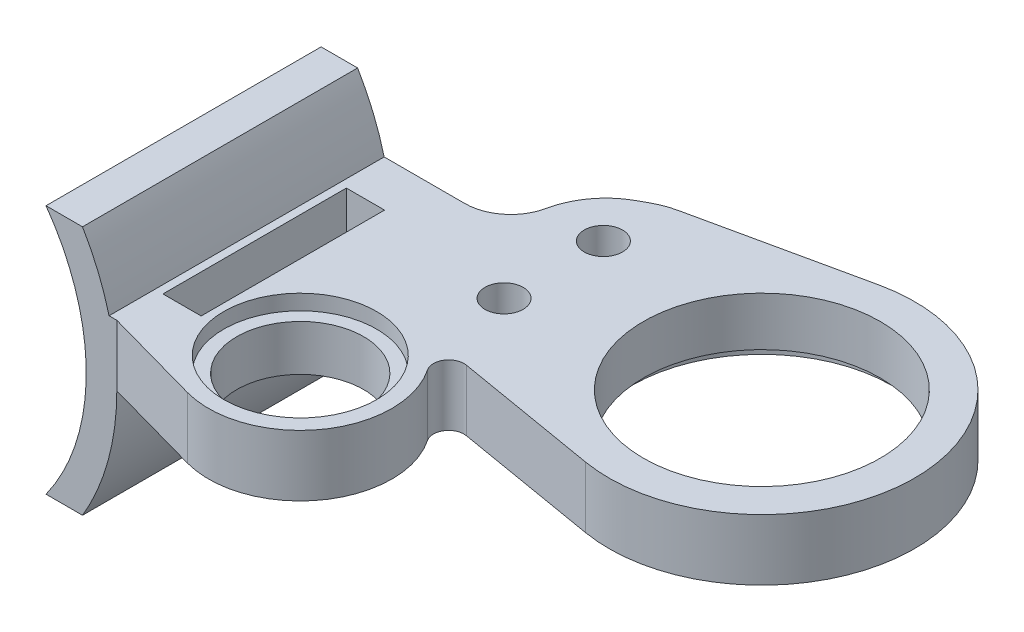
SolidWorks part; units mm, degrees
ref_plane "Front Plane" through (0, 0, 0) normal (0, 0, 1) x (1, 0, 0)
ref_plane "Top Plane" through (0, 0, 0) normal (0, 1, 0) x (1, 0, 0)
ref_plane "Right Plane" through (0, 0, 0) normal (1, 0, 0) x (0, 0, -1)
sketch "草图1" plane through (0, 0, 0) normal (0, 0, 1) x (1, 0, 0)
  line L6 (13.755, 8.1732) -> (11.3666, 8.1732)
  line L7 (11.3666, -8.1732) -> (13.755, -8.1732)
  arc A0 (11.3666, 8.1732) -> (11.3666, -8.1732) centre (0, 0) cw
  arc A1 (13.755, 8.1732) -> (13.755, -8.1732) centre (0, 0) cw
  dimension "D1" = 14
  dimension "D2" = 16
extrude "凸台-拉伸1" add sketch "草图1" along normal blind 18
sketch "草图3" plane through (0, 0, 0) normal (0, 1, 0) x (1, 0, 0)
  line L1 (16, -18) -> (14.8775, -18)
  line L4 (16, -18) -> (22.39, -19.7799)
  line L5 (13.755, -18) -> (16, -18) construction
  line L6 (16, -18) -> (16, 0) construction
  line L7 (14.8775, -18) -> (14.8775, 0)
  line L8 (16, 0) -> (13.755, 0) construction
  line L9 (14.8775, 0) -> (16, 0)
  line L12 (16.0173, -15) -> (18.5173, -15)
  line L13 (16.0173, -15) -> (16.0173, -3)
  line L14 (16.0173, -3) -> (18.5173, -3)
  line L15 (18.5173, -15) -> (18.5173, -3)
  line L16 (16.0173, -15) -> (18.5173, -3) construction
  line L17 (16.0173, -3) -> (18.5173, -15) construction
  line L18 (39.371, -10.7007) -> (26.3968, -8.4995)
  line L23 (27.4261, 6.433) -> (38.9205, 8.9304)
  line L24 (27.4261, 12.6834) -> (27.4261, -9.9467) construction
  line L25 (16, 0) -> (23.607, 0)
  line L29 (23.607, 0) -> (23.607, 4.3535)
  line L30 (23.607, 4.3535) -> (27.4261, 6.433)
  circle A1 centre (24, -14) radius 4.15
  arc A3 (39.371, -10.7007) -> (38.9205, 8.9304) centre (41.0437, -0.8416) ccw
  circle A4 centre (41.0437, -0.8416) radius 7.75
  circle A9 centre (41.0437, -0.8416) radius 14 construction
  circle A10 centre (27.4261, -4.0916) radius 1.25
  circle A11 centre (27.4261, 2.4084) radius 1.25
  arc A12 (26.3968, -8.4995) -> (22.39, -19.7799) centre (24, -14) cw
  point P16 (17.2673, -9)
  point P52 (14.8775, -9)
  dimension "D3" = 8.3
  dimension "D6" = 10
  dimension "D7" = 15.5
  dimension "D10" = 6
  dimension "D19" = 28
  dimension "D21" = 2.5
  dimension "D22" = 2.5
  dimension "D1" = 4
  dimension "D4" = 12
  dimension "D5" = 2.5
  dimension "4.5" = 8
  dimension "D20" = 6.5
extrude "凸台-拉伸2" add sketch "草图3" along normal blind 4
fillet "圆角1" radius 5 2 edges at (23.607, 2, -4.3535) (27.4261, 2, -6.433)
fillet "圆角2" radius 3 1 edges at (23.607, 2, 0)
fillet "圆角3" radius 1 1 edges at (26.3968, 2, 8.4995)
sketch "草图7" plane through (0, 0, 0) normal (0, -1, 0) x (1, 0, 0)
  circle A0 centre (41.0437, 0.8416) radius 8.5
  dimension "D1" = 17
extrude "切除-拉伸2" cut sketch "草图7" against normal blind 0.8
sketch "草图8" plane through (0, 4, 0) normal (0, 1, 0) x (1, 0, 0)
  circle A0 centre (24, -14) radius 5
  dimension "D1" = 10
extrude "切除-拉伸3" cut sketch "草图8" against normal blind 1
